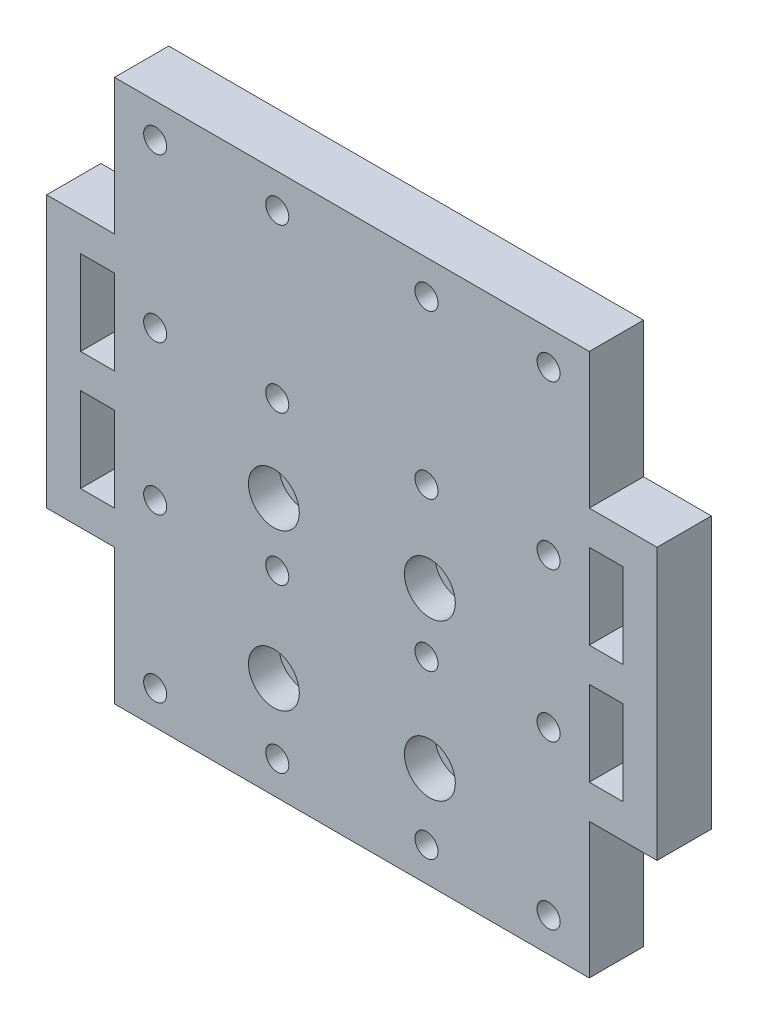
SolidWorks part; units mm, degrees
ref_plane "前视基准面" through (0, 0, 0) normal (0, 0, 1) x (1, 0, 0)
ref_plane "上视基准面" through (0, 0, 0) normal (0, 1, 0) x (1, 0, 0)
ref_plane "右视基准面" through (0, 0, 0) normal (1, 0, 0) x (0, 0, -1)
sketch "草图1" plane through (0, 0, 0) normal (0, 0, 1) x (1, 0, 0)
  line L0 (-32.3179, 17.0488) -> (-26.3179, 17.0488) construction
  line L1 (-32.3179, 22.0488) -> (37.6821, 22.0488)
  line L2 (-32.3179, 22.0488) -> (-32.3179, -57.9512)
  line L3 (-32.3179, -57.9512) -> (37.6821, -57.9512)
  line L4 (37.6821, 22.0488) -> (37.6821, -57.9512)
  line L5 (2.6821, 22.0488) -> (2.6821, -57.9512) construction
  line L10 (-32.3179, -17.9512) -> (37.6821, -17.9512) construction
  circle A0 centre (-26.3179, 17.0488) radius 1.7
  circle A1 centre (-8.3179, 17.0488) radius 1.7
  circle A2 centre (-26.3179, -6.9512) radius 1.7
  circle A3 centre (-8.3179, -6.9512) radius 1.7
  circle A4 centre (31.6821, -6.9512) radius 1.7
  circle A5 centre (13.6821, -6.9512) radius 1.7
  circle A6 centre (13.6821, 17.0488) radius 1.7
  circle A7 centre (31.6821, 17.0488) radius 1.7
  circle A8 centre (13.6821, -28.9512) radius 1.7
  circle A9 centre (31.6821, -28.9512) radius 1.7
  circle A10 centre (31.6821, -52.9512) radius 1.7
  circle A11 centre (13.6821, -52.9512) radius 1.7
  circle A12 centre (-26.3179, -28.9512) radius 1.7
  circle A13 centre (-8.3179, -28.9512) radius 1.7
  circle A14 centre (-8.3179, -52.9512) radius 1.7
  circle A15 centre (-26.3179, -52.9512) radius 1.7
  point P4 (-32.3179, 17.0488)
  dimension "D1" = 80
  dimension "D2" = 70
  dimension "D3" = 5
  dimension "D4" = 6
  dimension "D5" = 24
  dimension "D6" = 18
extrude "凸台-拉伸1" add sketch "草图1" along normal blind 8
sketch "草图2" plane through (0, 0, 0) normal (0, 0, -1) x (-1, 0, 0)
  line L0 (-33.3821, 17.0488) -> (-29.9821, 17.0488) construction
  line L1 (-37.6821, -17.9512) -> (32.3179, -17.9512) construction
  line L2 (-37.6821, -57.9512) -> (-37.6821, 22.0488) construction
  line L3 (32.3179, 22.0488) -> (32.3179, -57.9512) construction
  circle A0 centre (-31.6821, 17.0488) radius 1.7 construction
  circle A1 centre (-31.6821, 17.0488) radius 3.75
  circle A2 centre (-13.6821, 17.0488) radius 3.75
  circle A3 centre (8.3179, 17.0488) radius 3.75
  circle A4 centre (26.3179, 17.0488) radius 3.75
  circle A5 centre (-31.6821, -6.9512) radius 3.75
  circle A6 centre (-13.6821, -6.9512) radius 3.75
  circle A7 centre (8.3179, -6.9512) radius 3.75
  circle A8 centre (26.3179, -6.9512) radius 3.75
  circle A9 centre (-31.6821, -28.9512) radius 3.75
  circle A10 centre (-13.6821, -28.9512) radius 3.75
  circle A11 centre (8.3179, -28.9512) radius 3.75
  circle A12 centre (26.3179, -28.9512) radius 3.75
  circle A13 centre (26.3179, -52.9512) radius 3.75
  circle A14 centre (8.3179, -52.9512) radius 3.75
  circle A15 centre (-13.6821, -52.9512) radius 3.75
  circle A16 centre (-31.6821, -52.9512) radius 3.75
extrude "切除-拉伸1" cut sketch "草图2" against normal blind 4.5
sketch "草图3" plane through (0, 0, 8) normal (0, 0, 1) x (1, 0, 0)
  line L0 (-32.3179, -17.9512) -> (37.6821, -17.9512) construction
  line L1 (-32.3179, 22.0488) -> (-32.3179, -57.9512) construction
  line L2 (37.6821, -57.9512) -> (37.6821, 22.0488) construction
  line L3 (37.6821, 2.0488) -> (37.6821, -37.9512)
  line L4 (2.6821, 22.0488) -> (2.6821, -57.9512) construction
  line L5 (37.6821, 2.0488) -> (47.6821, 2.0488)
  line L6 (37.6821, 2.0488) -> (37.6821, -37.9512)
  line L7 (37.6821, -37.9512) -> (47.6821, -37.9512)
  line L8 (47.6821, 2.0488) -> (47.6821, -37.9512)
  line L9 (37.6821, -2.9512) -> (42.6821, -2.9512)
  line L10 (37.6821, -2.9512) -> (37.6821, -15.4512)
  line L11 (37.6821, -15.4512) -> (42.6821, -15.4512)
  line L12 (42.6821, -2.9512) -> (42.6821, -15.4512)
  line L13 (37.6821, -20.4512) -> (42.6821, -20.4512)
  line L14 (37.6821, -20.4512) -> (37.6821, -32.9512)
  line L15 (37.6821, -32.9512) -> (42.6821, -32.9512)
  line L16 (42.6821, -20.4512) -> (42.6821, -32.9512)
  line L17 (37.6821, 22.0488) -> (-32.3179, 22.0488) construction
  line L18 (-32.3179, -57.9512) -> (37.6821, -57.9512) construction
  line L19 (-32.3179, -32.9512) -> (-37.3179, -32.9512)
  line L20 (-37.3179, -20.4512) -> (-37.3179, -32.9512)
  line L21 (-32.3179, -20.4512) -> (-37.3179, -20.4512)
  line L22 (-32.3179, -20.4512) -> (-32.3179, -32.9512)
  line L23 (-32.3179, -15.4512) -> (-37.3179, -15.4512)
  line L24 (-37.3179, -2.9512) -> (-37.3179, -15.4512)
  line L25 (-32.3179, -2.9512) -> (-37.3179, -2.9512)
  line L26 (-32.3179, -2.9512) -> (-32.3179, -15.4512)
  line L27 (-32.3179, -37.9512) -> (-42.3179, -37.9512)
  line L28 (-42.3179, 2.0488) -> (-42.3179, -37.9512)
  line L29 (-32.3179, 2.0488) -> (-42.3179, 2.0488)
  line L30 (-32.3179, 2.0488) -> (-32.3179, -37.9512)
  point P9 (37.6821, -17.9512)
  point P11 (37.6821, -2.9512)
  point P16 (37.6821, -20.4512)
  line M23 (-32.3179, 22.0488) -> (-32.3179, -57.9512)
  line M25 (37.6821, -57.9512) -> (37.6821, 22.0488)
  dimension "D1" = 40
  dimension "D2" = 10
  dimension "D3" = 5
  dimension "D4" = 12.5
  dimension "D5" = 5
  dimension "D6" = 2.5
  dimension "D7" = 12.5
  dimension "D8" = 5
extrude "凸台-拉伸2" add sketch "草图3" against normal blind 8 contours L13 L16 L15 L7 L8 L5 L6 L9 L12 L11 M25 | L29 L28 L27 L19 L20 L21 L23 L24 L25 M23
sketch "草图4" plane through (0, 0, 8) normal (0, 0, 1) x (1, 0, 0)
  line L0 (2.6821, -57.9512) -> (2.6821, -42.9512) construction
  line L1 (-32.3179, -57.9512) -> (37.6821, -57.9512) construction
  line L2 (-8.8179, -42.9512) -> (14.1821, -42.9512)
  circle A0 centre (-8.8179, -42.9512) radius 1.7
  circle A1 centre (14.1821, -42.9512) radius 1.7
  point P7 (2.6821, -42.9512)
  dimension "D1" = 15
  dimension "D2" = 23
extrude "切除-拉伸2" cut sketch "草图4" against normal blind 20 contours A0 | A1
sketch "草图6" plane through (0, 0, 8) normal (0, 0, 1) x (1, 0, 0)
  line L0 (-8.8179, -44.6512) -> (-8.8179, -41.2512) construction
  line L1 (14.1821, -44.6512) -> (14.1821, -41.2512) construction
  circle A0 centre (-8.8179, -42.9512) radius 1.7 construction
  circle A1 centre (14.1821, -42.9512) radius 1.7 construction
  circle A2 centre (-8.8179, -42.9512) radius 3.75
  circle A3 centre (14.1821, -42.9512) radius 3.75
extrude "切除-拉伸4" cut sketch "草图6" against normal blind 4.5
sketch "草图7" plane through (0, 0, 0) normal (0, 0, -1) x (-1, 0, 0)
  line L0 (-12.4821, -42.9512) -> (-15.8821, -42.9512) construction
  line L1 (-14.1821, -42.9512) -> (-14.1821, -19.9512) construction
  line L2 (7.1179, -42.9512) -> (10.5179, -42.9512) construction
  line L3 (8.8179, -42.9512) -> (8.8179, -19.9512) construction
  circle A0 centre (-14.1821, -42.9512) radius 1.7 construction
  circle A1 centre (-14.1821, -19.9512) radius 1.9382
  circle A2 centre (8.8179, -42.9512) radius 1.7 construction
  circle A3 centre (8.8179, -19.9512) radius 1.7
  dimension "D1" = 23
extrude "切除-拉伸5" cut sketch "草图7" against normal blind 10
sketch "草图8" plane through (0, 0, 8) normal (0, 0, 1) x (1, 0, 0)
  line L0 (-8.8179, -18.2512) -> (-8.8179, -21.6512) construction
  line L1 (14.1821, -18.013) -> (14.1821, -21.8894) construction
  circle A0 centre (-8.8179, -19.9512) radius 1.7 construction
  circle A1 centre (14.1821, -19.9512) radius 1.9382 construction
  circle A2 centre (-8.8179, -19.9512) radius 3.75
  circle A3 centre (14.1821, -19.9512) radius 3.75
extrude "切除-拉伸6" cut sketch "草图8" against normal blind 4.5
